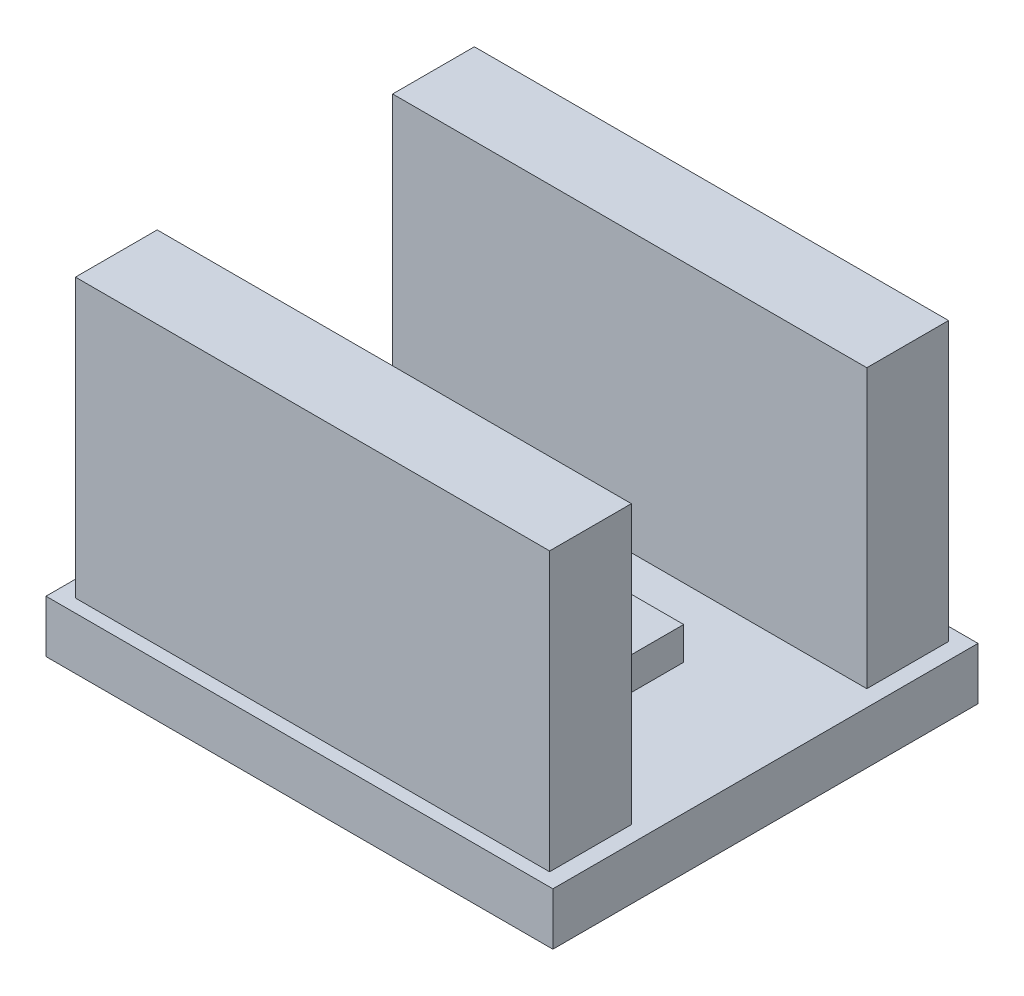
SolidWorks part; units mm, degrees
ref_plane "Front Plane" through (0, 0, 0) normal (0, 0, 1) x (1, 0, 0)
ref_plane "Top Plane" through (0, 0, 0) normal (0, 1, 0) x (1, 0, 0)
ref_plane "Right Plane" through (0, 0, 0) normal (1, 0, 0) x (0, 0, -1)
other "Configuration Table"
sketch "Sketch1" plane through (0, 0, 0) normal (0, 1, 0) x (1, 0, 0)
  line L1 (0, 0) -> (15.5, 0)
  line L2 (0, 0) -> (0, 13)
  line L3 (0, 13) -> (15.5, 13)
  line L4 (15.5, 0) -> (15.5, 13)
extrude "PCB" add sketch "Sketch1" along normal blind 1.6
sketch "Sketch2" plane through (0, 0, 0) normal (0, 1, 0) x (1, 0, 0)
  line L1 (0.5, 0.4) -> (15, 0.4)
  line L2 (0.5, 0.4) -> (0.5, 2.9)
  line L3 (0.5, 2.9) -> (15, 2.9)
  line L4 (15, 0.4) -> (15, 2.9)
extrude "Header_HV" add sketch "Sketch2" along normal blind 8.5 from offset 1.6
sketch "Sketch3" plane through (0, 0, 0) normal (0, 1, 0) x (1, 0, 0)
  line L1 (0.5, 10.1) -> (15, 10.1)
  line L2 (0.5, 10.1) -> (0.5, 12.6)
  line L3 (0.5, 12.6) -> (15, 12.6)
  line L4 (15, 10.1) -> (15, 12.6)
extrude "Header_LV" add sketch "Sketch3" along normal blind 8.5 from offset 1.6
sketch "Sketch4" plane through (0, 0, 0) normal (0, 1, 0) x (1, 0, 0)
  line L1 (4, 5) -> (11.5, 5)
  line L2 (4, 5) -> (4, 8)
  line L3 (4, 8) -> (11.5, 8)
  line L4 (11.5, 5) -> (11.5, 8)
extrude "MOSFETs" add sketch "Sketch4" along normal blind 1 from offset 1.6
